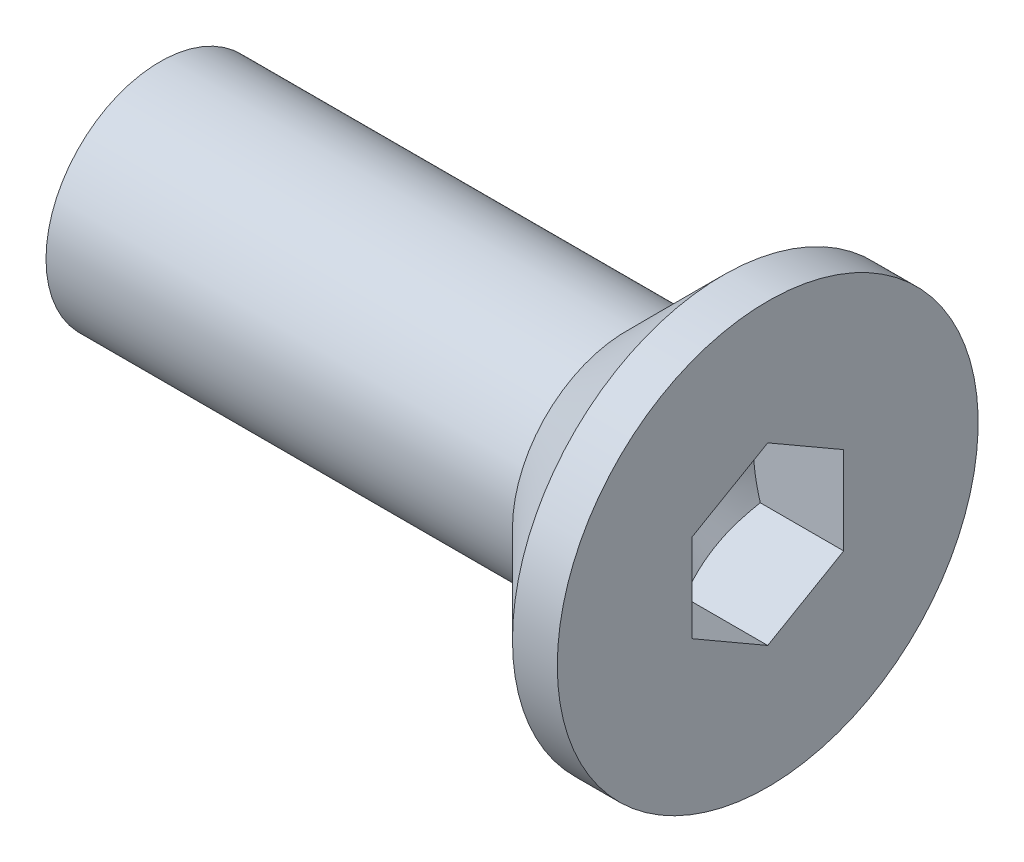
SolidWorks part; units mm, degrees
ref_plane "Спереди" through (0, 0, 0) normal (0, 0, 1) x (1, 0, 0)
ref_plane "Сверху" through (0, 0, 0) normal (0, 1, 0) x (1, 0, 0)
ref_plane "Справа" through (0, 0, 0) normal (1, 0, 0) x (0, 0, -1)
sketch "Sk1" plane through (0, 0, 0) normal (0, 0, 1) x (1, 0, 0)
  line L0 (0, 0) -> (2.5324, 0) construction
  line L1 (-6.14, 0) -> (1.86, 0)
  line L2 (0, 1.5) -> (-6.14, 1.5)
  line L3 (0, 1.5) -> (1.27, 2.77)
  line L4 (1.27, 2.77) -> (1.86, 2.77)
  line L5 (-6.14, 1.5) -> (-6.14, 0)
  line L6 (0, 1.5) -> (0, 0) construction
  line L7 (0, -1.5) -> (1.27, -2.77) construction
  line L8 (1.86, 2.77) -> (1.86, 0)
  dimension "d" = 3
  dimension "l" = 8
  dimension "dk" = 5.54
  dimension "k" = 1.86
  dimension "ang" = 90
revolve "Body" add sketch "Sk1" angle 360 about L0
cosmetic thread "Thrd" parameters "lr"=6.1, "dr"=2.459
sketch "Sk3" plane through (0, 0, 0) normal (0, 0, 1) x (1, 0, 0)
  line L0 (2.4166, 0) -> (0.0952, 0) construction
  line L2 (0.76, 1.1515) -> (0.0952, 0)
  line L3 (0.76, -1.1515) -> (0.0952, 0) construction
  line L4 (1.86, -2.77) -> (1.86, 2.77) construction
  dimension "D1" = 120
  dimension "t" = 1.1
  dimension "e" = 2.303
surface "Hole" sketch "Sk3" parameters "D1"=360
sketch "Sk2" plane through (1.86, 0, -1.86) normal (-1, 0, 0) x (0, 0, 1)
  line L1 (1.86, 1.1547) -> (0.86, 0.5774)
  line L2 (0.86, 0.5774) -> (0.86, -0.5774)
  line L3 (0.86, -0.5774) -> (1.86, -1.1547)
  line L4 (1.86, -1.1547) -> (2.86, -0.5774)
  line L6 (2.86, -0.5774) -> (2.86, 0.5774)
  line L7 (2.86, 0.5774) -> (1.86, 1.1547)
  circle A0 centre (1.86, 0) radius 1 construction
  dimension "s" = 2
extrude "Slot" cut sketch "Sk2" along normal up to surface (1.0982 mm away)
sketch "NoToCut" plane through (0, 0, 0) normal (0, 0, 1) x (1, 0, 0)
  line L0 (-0.04, 0.5893) -> (-0.04, -0.4525)
  line L2 (1.86, -2.77) -> (1.86, 2.77) construction
  dimension "lg" = 1.9
fillet "Head Fillet" [suppressed] radius 0.1
delete or keep bodies "ClearBody" type delete bodies bodies 122
equation "\"lr@Thrd\" = \"l@Sk1\" - \"lg@NoToCut\""
